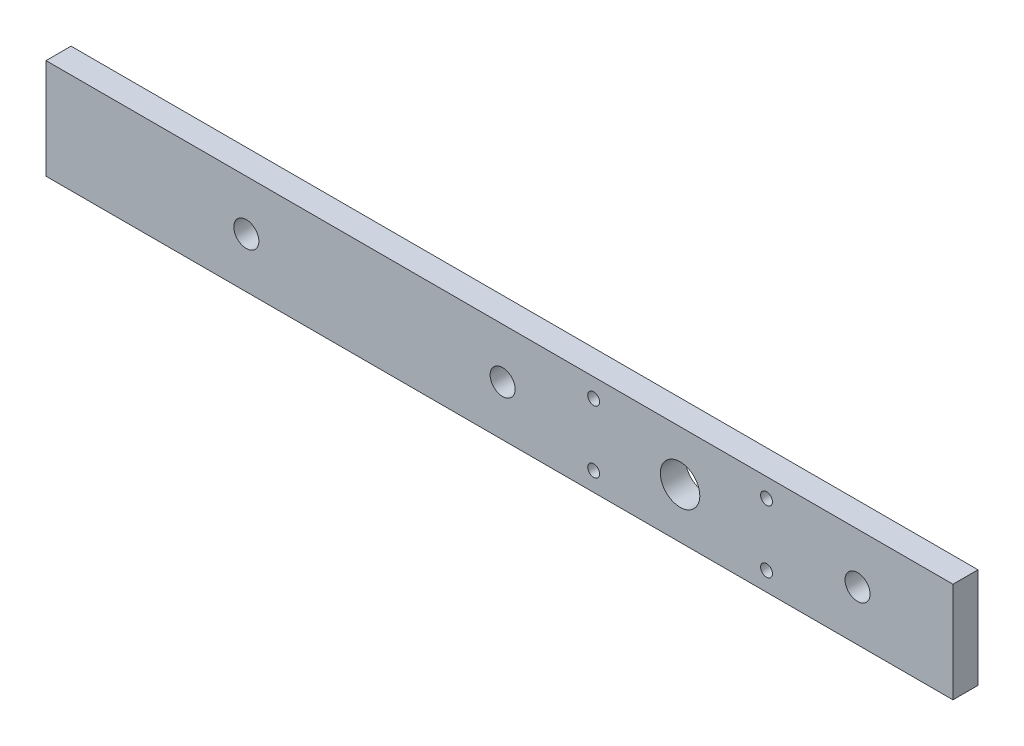
SolidWorks part; units mm, degrees
ref_plane "Front Plane" through (0, 0, 0) normal (0, 0, 1) x (1, 0, 0)
ref_plane "Top Plane" through (0, 0, 0) normal (0, 1, 0) x (1, 0, 0)
ref_plane "Right Plane" through (0, 0, 0) normal (1, 0, 0) x (0, 0, -1)
sketch "Sketch1" plane through (0, 0, 0) normal (1, 0, 0) x (0, 0, -1)
  line L1 (0, 0) -> (6.35, 0)
  line L2 (0, 0) -> (0, 25.4)
  line L3 (0, 25.4) -> (6.35, 25.4)
  line L4 (6.35, 0) -> (6.35, 25.4)
  dimension "D1" = 25.4
  dimension "D2" = 6.35
extrude "Boss-Extrude1" add sketch "Sketch1" along normal blind 304.8
sketch "Sketch2" plane through (0, 0, 0) normal (0, 0, 1) x (1, 0, 0)
  line L0 (304.8, 12.7) -> (160.8, 12.7) construction
  line L1 (304.8, 25.4) -> (304.8, 0) construction
  line L2 (160.8, 12.7) -> (50.8, 12.7) construction
  line L3 (0, 25.4) -> (0, 0) construction
  line L6 (115.8, 12.7) -> (205.8, 12.7) construction
  circle A0 centre (160.8, 12.7) radius 5
  circle A1 centre (50.8, 12.7) radius 3.175
  circle A4 centre (115.8, 12.7) radius 3.175
  circle A5 centre (205.8, 12.7) radius 3.175
  point P16 (160.8, 12.7)
  dimension "D1" = 10
  dimension "D3" = 6.35
  dimension "D8" = 6.35
  dimension "D2" = 90
  dimension "D4" = 110
  dimension "D5" = 50.8
extrude "Cut-Extrude1" cut sketch "Sketch2" against normal through all
sketch "Sketch4" plane through (0, 0, 0) normal (0, 0, 1) x (1, 0, 0)
  line L0 (138.8797, 12.7) -> (160.8, 12.7) construction
  line L1 (160.8, 12.7) -> (182.7203, 12.7) construction
  line L2 (304.8, 25.4) -> (0, 25.4) construction
  line L3 (138.8797, 4.8) -> (182.7203, 4.8) construction
  line L4 (138.8797, 4.8) -> (138.8797, 20.6) construction
  line L5 (138.8797, 20.6) -> (182.7203, 20.6) construction
  line L6 (182.7203, 4.8) -> (182.7203, 20.6) construction
  circle A0 centre (182.7203, 12.7) radius 1.5 construction
  circle A1 centre (138.8797, 12.7) radius 1.5 construction
  circle A2 centre (138.8797, 20.6) radius 1.5
  circle A3 centre (182.7203, 20.6) radius 1.5
  circle A4 centre (182.7203, 4.8) radius 1.5
  circle A5 centre (138.8797, 4.8) radius 1.5
  circle A6 centre (138.8797, 20.6) radius 1.8 construction
  point P10 (138.8797, 12.7)
  dimension "D2" = 3
  dimension "D3" = 3
  dimension "D4" = 3.6
  dimension "D1" = 43.8406
  dimension "D5" = 3
extrude "Cut-Extrude2" cut sketch "Sketch4" against normal through all
sketch "Sketch5" plane through (0, 0, 0) normal (0, 0, 1) x (1, 0, 0)
  line L0 (304.8, 12.7) -> (292.1, 12.7) construction
  line L1 (304.8, 25.4) -> (304.8, 0) construction
  line L2 (292.1, 12.7) -> (241.3, 12.7) construction
  circle A0 centre (241.3, 12.7) radius 3.175
  circle A1 centre (292.1, 12.7) radius 3.175
  dimension "D3" = 6.35
  dimension "D1" = 12.7
  dimension "D2" = 50.8
extrude "Cut-Extrude3" cut sketch "Sketch5" against normal through all
sketch "Sketch6" plane through (0, 0, 0) normal (0, 0, 1) x (1, 0, 0)
  line L1 (304.8, 0) -> (0, 0) construction
  line L2 (304.8, 25.4) -> (230, 25.4)
  line L3 (304.8, 25.4) -> (304.8, 0)
  line L4 (304.8, 0) -> (230, 0)
  line L6 (230, 25.4) -> (230, 0)
  line L7 (0, 25.4) -> (0, 0) construction
  dimension "D1" = 230
extrude "Cut-Extrude5" cut sketch "Sketch6" against normal blind 10
